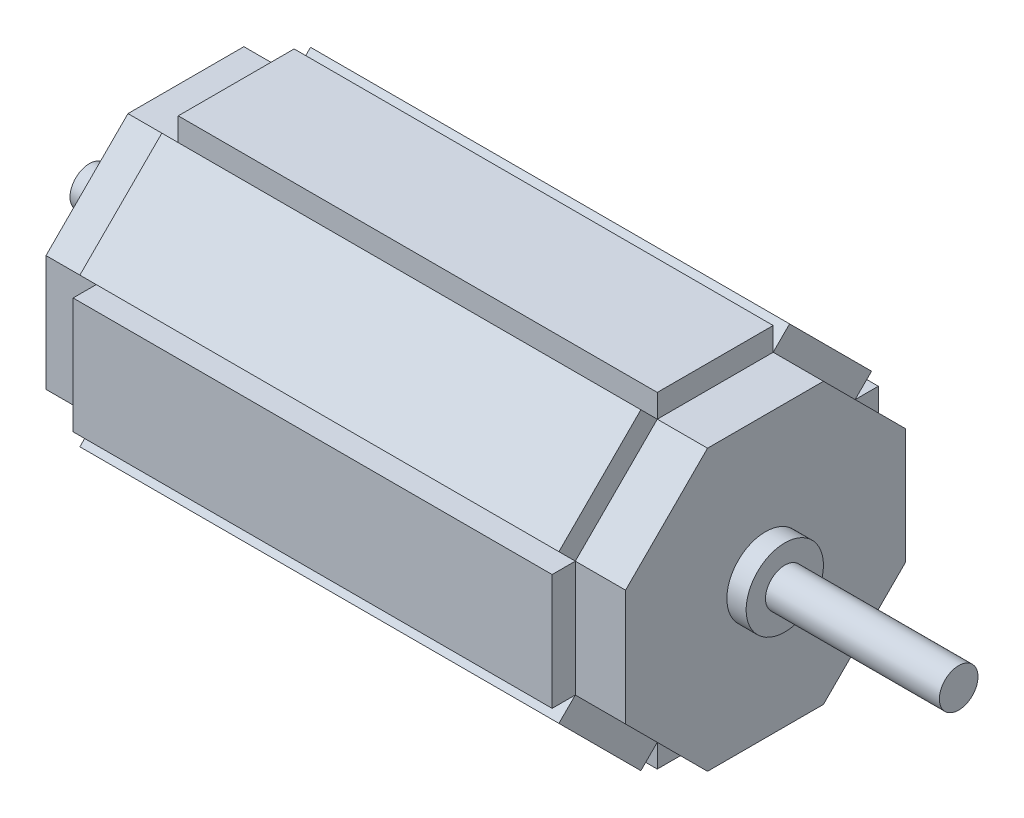
SolidWorks part; units mm, degrees
ref_plane "前视基准面" through (0, 0, 0) normal (0, 0, 1) x (1, 0, 0)
ref_plane "上视基准面" through (0, 0, 0) normal (0, 1, 0) x (1, 0, 0)
ref_plane "右视基准面" through (0, 0, 0) normal (1, 0, 0) x (0, 0, -1)
other "Configuration Table"
sketch "草图1" plane through (0, 0, 0) normal (1, 0, 0) x (0, 0, -1)
  line L1 (7.2426, -3) -> (7.2426, 3)
  line L2 (7.2426, 3) -> (3, 7.2426)
  line L3 (3, 7.2426) -> (-3, 7.2426)
  line L4 (-3, 7.2426) -> (-7.2426, 3)
  line L5 (-7.2426, 3) -> (-7.2426, -3)
  line L6 (-7.2426, -3) -> (-3, -7.2426)
  line L7 (-3, -7.2426) -> (3, -7.2426)
  line L8 (3, -7.2426) -> (7.2426, -3)
  circle A0 centre (0, 0) radius 7.2426 construction
  dimension "D1" = 6
extrude "凸台-拉伸1" add sketch "草图1" along normal blind 30
sketch "草图2" plane through (0, 7.2426, 0) normal (0, 1, 0) x (1, 0, 0)
  line L0 (9.4384, -2.3461) -> (9.352, -2.1662)
  line L1 (9.352, -2.1662) -> (9.8774, -1.7488)
  line L2 (9.8774, -1.7488) -> (9.9997, -1.8064)
  line L3 (11.1224, -1.9863) -> (11.4319, -2.0078)
  line L4 (11.4319, -2.0078) -> (11.6478, -2.0151)
  line L5 (11.6478, -2.0151) -> (11.655, -1.5833)
  line L6 (9.9134, -0.9068) -> (9.8702, -0.7341)
  line L7 (9.8702, -0.7341) -> (10.0933, -0.5901)
  line L8 (10.0933, -0.5901) -> (10.1005, -0.5829)
  line L9 (9.8126, 0.6981) -> (10.2732, 1.1299)
  line L10 (11.6406, 0.7557) -> (11.6765, 0.7629)
  line L11 (11.6765, 0.7629) -> (11.6622, 0.9284)
  line L12 (11.5902, 1.4249) -> (11.9284, 1.684)
  line L13 (11.9284, 1.684) -> (11.5686, 1.7272)
  line L14 (11.5686, 1.7272) -> (10.5467, 1.828)
  line L15 (9.6975, 1.828) -> (9.6399, 1.828)
  line L16 (9.6399, 1.828) -> (9.5247, 2.0151)
  line L17 (9.5247, 2.0151) -> (10.1365, 2.4037)
  line L18 (12.3746, 2.0367) -> (12.5186, 2.051)
  line L19 (12.5186, 2.051) -> (12.5617, 1.8711)
  line L20 (12.5617, 1.8711) -> (12.1515, 1.648)
  line L21 (12.0292, 1.1011) -> (11.9644, 0)
  line L22 (11.9788, -1.9647) -> (11.9788, -2.0294)
  line L23 (11.9788, -2.0294) -> (12.6265, -2.0294)
  line L24 (12.6265, -2.0294) -> (12.6625, -2.159)
  line L25 (12.6625, -2.159) -> (12.2451, -2.4541)
  line L26 (12.3386, -1.6264) -> (12.3962, -1.4897)
  line L27 (13.339, -1.7488) -> (13.3462, -1.3889)
  line L28 (13.3606, -0.6909) -> (12.5761, -0.5829)
  line L29 (12.5761, -0.5829) -> (12.5401, -0.4822)
  line L30 (12.5401, -0.4822) -> (12.8496, -0.2591)
  line L31 (13.2886, 0.3886) -> (13.5261, 0.6621)
  line L32 (12.792, 0.7197) -> (12.7489, 0.8564)
  line L33 (12.7489, 0.8564) -> (12.9216, 0.9715)
  line L34 (12.9216, 0.9715) -> (12.9288, 1.0579)
  line L35 (12.9288, 1.0579) -> (12.9, 1.4249)
  line L36 (12.7057, 2.0655) -> (13.0727, 2.4037)
  line L37 (13.0727, 2.4037) -> (13.1231, 2.3533)
  line L38 (13.4613, 2.1662) -> (13.6197, 2.1302)
  line L39 (14.0802, 2.0583) -> (14.4473, 2.3821)
  line L40 (14.4473, 2.3821) -> (14.548, 2.2741)
  line L41 (14.548, 2.2741) -> (14.5336, 2.2454)
  line L42 (14.3249, 0.5829) -> (14.109, 0.3742)
  line L43 (14.109, 0.3742) -> (14.0011, 0.403)
  line L44 (14.0011, 0.403) -> (14.0011, 0.5757)
  line L45 (14.0011, 0.5757) -> (13.7276, 0.6333)
  line L46 (13.7276, 0.6333) -> (13.6916, 0.5038)
  line L47 (13.6412, -1.7632) -> (13.6485, -1.8279)
  line L48 (13.6485, -1.8279) -> (14.145, -1.9215)
  line L49 (14.1306, -0.4174) -> (14.5984, -0.0648)
  line L50 (14.5984, -0.0648) -> (14.6632, -0.1799)
  line L51 (14.4473, -1.8208) -> (14.4688, -1.9791)
  line L52 (14.4688, -1.9791) -> (14.8935, -2.0223)
  line L53 (14.8935, -2.0223) -> (14.951, -2.1086)
  line L54 (14.951, -2.1086) -> (14.5336, -2.3605)
  line L55 (11.6765, -0.6837) -> (11.6765, 0.4534)
  line L56 (11.2303, 0.511) -> (10.777, 0.5613)
  line L57 (10.777, 0.5613) -> (10.3164, 0.5829)
  line L58 (11.3527, -0.6909) -> (11.6765, -0.6837)
  line L59 (8.6618, -2.4842) -> (8.6618, 2.5158) construction
  spline S0 degree 3 poles (12.2451, -2.4541) (11.9788, -2.3917) (11.4463, -2.2669) (10.5755, -2.2669) knots 0 0 0 0 1 1 1 1
  spline S1 degree 3 poles (10.5755, -2.2669) (10.3955, -2.2669) (10.0357, -2.2669) (9.4384, -2.3461) knots 1 1 1 1 2 2 2 2
  spline S2 degree 3 poles (9.9997, -1.8064) (10.0765, -1.8399) (10.23, -1.9071) (10.669, -1.9503) knots 5 5 5 5 6 6 6 6
  spline S3 degree 3 poles (10.669, -1.9503) (10.7698, -1.9599) (10.9713, -1.9791) (11.1224, -1.9863) knots 6 6 6 6 7 7 7 7
  spline S4 degree 3 poles (11.655, -1.5833) (11.6598, -1.4537) (11.6694, -1.1946) (11.6622, -1.0003) knots 10 10 10 10 11 11 11 11
  spline S5 degree 3 poles (11.6622, -1.0003) (11.4631, -0.962) (11.0648, -0.8852) (10.4315, -0.8852) knots 11 11 11 11 12 12 12 12
  spline S6 degree 3 poles (10.4315, -0.8852) (10.3452, -0.8852) (10.1725, -0.8852) (9.9134, -0.9068) knots 12 12 12 12 13 13 13 13
  spline S7 degree 3 poles (10.1005, -0.5829) (10.0981, -0.523) (10.0933, -0.403) (10.0789, -0.2123) knots 16 16 16 16 17 17 17 17
  spline S8 degree 3 poles (10.0789, -0.2123) (10.0741, -0.1487) (10.0645, -0.0216) (10.0285, 0.1295) knots 17 17 17 17 18 18 18 18
  spline S9 degree 3 poles (10.0285, 0.1295) (10.0165, 0.1967) (9.9925, 0.331) (9.9494, 0.4606) knots 18 18 18 18 19 19 19 19
  spline S10 degree 3 poles (9.9494, 0.4606) (9.9349, 0.5038) (9.9062, 0.5901) (9.8126, 0.6981) knots 19 19 19 19 20 20 20 20
  spline S11 degree 3 poles (10.2732, 1.1299) (10.3356, 1.0675) (10.4603, 0.9428) (10.7194, 0.878) knots 21 21 21 21 22 22 22 22
  spline S12 degree 3 poles (10.7194, 0.878) (10.8417, 0.8468) (11.0864, 0.7844) (11.6406, 0.7557) knots 22 22 22 22 23 23 23 23
  spline S13 degree 3 poles (11.6622, 0.9284) (11.6598, 0.9692) (11.655, 1.0507) (11.6406, 1.1839) knots 25 25 25 25 26 26 26 26
  spline S14 degree 3 poles (11.6406, 1.1839) (11.6358, 1.2283) (11.6262, 1.317) (11.5902, 1.4249) knots 26 26 26 26 27 27 27 27
  spline S15 degree 3 poles (10.5467, 1.828) (10.4747, 1.8351) (10.3308, 1.8495) (10.1221, 1.8495) knots 30 30 30 30 31 31 31 31
  spline S16 degree 3 poles (10.1221, 1.8495) (10.0477, 1.8495) (9.899, 1.8495) (9.6975, 1.828) knots 31 31 31 31 32 32 32 32
  spline S17 degree 3 poles (10.1365, 2.4037) (10.2036, 2.3365) (10.338, 2.2022) (10.6978, 2.1158) knots 35 35 35 35 36 36 36 36
  spline S18 degree 3 poles (10.6978, 2.1158) (10.7793, 2.0966) (10.9425, 2.0583) (11.2879, 2.0367) knots 36 36 36 36 37 37 37 37
  spline S19 degree 3 poles (11.2879, 2.0367) (11.3719, 2.0271) (11.5398, 2.0079) (11.8565, 2.0079) knots 37 37 37 37 38 38 38 38
  spline S20 degree 3 poles (11.8565, 2.0079) (11.9524, 2.0079) (12.1443, 2.0079) (12.3746, 2.0367) knots 38 38 38 38 39 39 39 39
  spline S21 degree 3 poles (12.1515, 1.648) (12.1179, 1.5641) (12.0508, 1.3962) (12.0292, 1.1011) knots 42 42 42 42 43 43 43 43
  spline S22 degree 3 poles (11.9644, 0) (11.962, -0.0911) (11.9572, -0.2735) (11.9572, -0.8132) knots 44 44 44 44 45 45 45 45
  spline S23 degree 3 poles (11.9572, -0.8132) (11.9572, -1.0051) (11.9572, -1.3889) (11.9788, -1.9647) knots 45 45 45 45 46 46 46 46
  spline S24 degree 3 poles (14.5336, -2.3605) (14.3705, -2.2981) (14.0442, -2.1734) (13.0511, -1.8567) knots 0 0 0 0 1 1 1 1
  spline S25 degree 3 poles (13.0511, -1.8567) (12.9719, -1.8327) (12.8136, -1.7848) (12.3386, -1.6264) knots 1 1 1 1 2 2 2 2
  spline S26 degree 3 poles (12.3962, -1.4897) (12.5665, -1.5401) (12.9072, -1.6409) (13.339, -1.7488) knots 3 3 3 3 4 4 4 4
  spline S27 degree 3 poles (13.3462, -1.3889) (13.3534, -1.257) (13.3678, -0.9931) (13.3606, -0.6909) knots 5 5 5 5 6 6 6 6
  spline S28 degree 3 poles (12.8496, -0.2591) (12.8832, -0.2927) (12.9504, -0.3598) (13.0727, -0.4066) knots 9 9 9 9 10 10 10 10
  spline S29 degree 3 poles (13.0727, -0.4066) (13.1135, -0.4222) (13.195, -0.4534) (13.3678, -0.475) knots 10 10 10 10 11 11 11 11
  spline S30 degree 3 poles (13.3678, -0.475) (13.3678, -0.3022) (13.3678, 0.0432) (13.2886, 0.3886) knots 11 11 11 11 12 12 12 12
  spline S31 degree 3 poles (13.5261, 0.6621) (13.3918, 0.6813) (13.1231, 0.7197) (12.792, 0.7197) knots 13 13 13 13 14 14 14 14
  spline S32 degree 3 poles (12.9, 1.4249) (12.8928, 1.4945) (12.8784, 1.6336) (12.8388, 1.7848) knots 18 18 18 18 19 19 19 19
  spline S33 degree 3 poles (12.8388, 1.7848) (12.8256, 1.8351) (12.7993, 1.9359) (12.7057, 2.0655) knots 19 19 19 19 20 20 20 20
  spline S34 degree 3 poles (13.1231, 2.3533) (13.1711, 2.3101) (13.267, 2.2238) (13.4613, 2.1662) knots 22 22 22 22 23 23 23 23
  spline S35 degree 3 poles (13.6197, 2.1302) (13.6916, 2.1134) (13.8355, 2.0798) (14.0802, 2.0583) knots 24 24 24 24 25 25 25 25
  spline S36 degree 3 poles (14.5336, 2.2454) (14.5049, 2.1926) (14.4473, 2.087) (14.4113, 1.9143) knots 28 28 28 28 29 29 29 29
  spline S37 degree 3 poles (14.4113, 1.9143) (14.3969, 1.8472) (14.3681, 1.7128) (14.3465, 1.4897) knots 29 29 29 29 30 30 30 30
  spline S38 degree 3 poles (14.3465, 1.4897) (14.3321, 1.3602) (14.3033, 1.1011) (14.3033, 0.9068) knots 30 30 30 30 31 31 31 31
  spline S39 degree 3 poles (14.3033, 0.9068) (14.3033, 0.854) (14.3033, 0.7484) (14.3249, 0.5829) knots 31 31 31 31 32 32 32 32
  spline S40 degree 3 poles (13.6916, 0.5038) (13.6652, 0.4126) (13.6125, 0.2303) (13.6125, -0.1727) knots 37 37 37 37 38 38 38 38
  spline S41 degree 3 poles (13.6125, -0.1727) (13.6101, -0.2207) (13.6053, -0.3167) (13.6053, -0.5973) knots 38 38 38 38 39 39 39 39
  spline S42 degree 3 poles (13.6053, -0.5973) (13.6053, -0.77) (13.6053, -1.1155) (13.6412, -1.7632) knots 39 39 39 39 40 40 40 40
  spline S43 degree 3 poles (14.145, -1.9215) (14.1546, -1.8663) (14.1738, -1.756) (14.1882, -1.4321) knots 42 42 42 42 43 43 43 43
  spline S44 degree 3 poles (14.1882, -1.4321) (14.193, -1.3458) (14.2026, -1.1731) (14.2026, -1.0507) knots 43 43 43 43 44 44 44 44
  spline S45 degree 3 poles (14.2026, -1.0507) (14.2026, -0.938) (14.2026, -0.7125) (14.1306, -0.4174) knots 44 44 44 44 45 45 45 45
  spline S46 degree 3 poles (14.6632, -0.1799) (14.6296, -0.2303) (14.5624, -0.331) (14.5192, -0.439) knots 47 47 47 47 48 48 48 48
  spline S47 degree 3 poles (14.5192, -0.439) (14.5049, -0.475) (14.4761, -0.5469) (14.4617, -0.7125) knots 48 48 48 48 49 49 49 49
  spline S48 degree 3 poles (14.4617, -0.7125) (14.4521, -0.8084) (14.4329, -1.0003) (14.4329, -1.353) knots 49 49 49 49 50 50 50 50
  spline S49 degree 3 poles (14.4329, -1.353) (14.4329, -1.4561) (14.4329, -1.6624) (14.4473, -1.8208) knots 50 50 50 50 51 51 51 51
  spline S50 degree 3 poles (14.0227, 0.8132) (14.0467, 1.0051) (14.0946, 1.3889) (14.0874, 1.8136) knots 4 4 4 4 5 5 5 5
  spline S51 degree 3 poles (13.2382, 0.9715) (13.3414, 0.9404) (13.5477, 0.878) (14.0227, 0.8132) knots 3 3 3 3 4 4 4 4
  spline S52 degree 3 poles (13.1591, 1.9503) (13.1663, 1.7608) (13.1807, 1.3818) (13.2382, 0.9715) knots 2 2 2 2 3 3 3 3
  spline S53 degree 3 poles (13.6448, 1.8999) (13.5141, 1.9191) (13.2526, 1.9575) (13.1591, 1.9503) knots 1 1 1 1 2 2 2 2
  spline S54 degree 3 poles (14.0874, 1.8136) (14.0706, 1.8231) (14.0371, 1.8424) (13.6448, 1.8999) knots 0 0 0 0 1 1 1 1
  spline S55 degree 3 poles (11.6765, 0.4534) (11.6286, 0.463) (11.5326, 0.4822) (11.2303, 0.511) knots 1 1 1 1 2 2 2 2
  spline S56 degree 3 poles (10.3164, 0.5829) (10.3164, 0.355) (10.3164, -0.1007) (10.4171, -0.5326) knots 4 4 4 4 5 5 5 5
  spline S57 degree 3 poles (10.4171, -0.5326) (10.4555, -0.5494) (10.5323, -0.5829) (10.669, -0.6189) knots 5 5 5 5 6 6 6 6
  spline S58 degree 3 poles (10.669, -0.6189) (10.7194, -0.6309) (10.8201, -0.6549) (11.0001, -0.6693) knots 6 6 6 6 7 7 7 7
  spline S59 degree 3 poles (11.0001, -0.6693) (11.06, -0.6741) (11.18, -0.6837) (11.3527, -0.6909) knots 7 7 7 7 8 8 8 8
  dimension "D1" = 5
sketch "草图3" plane through (0, 7.2426, 0) normal (0, 1, 0) x (1, 0, 0)
  line L0 (16.0742, -2.3589) -> (15.9878, -2.179)
  line L1 (15.9878, -2.179) -> (16.5131, -1.7616)
  line L2 (16.5131, -1.7616) -> (16.6355, -1.8191)
  line L3 (17.7582, -1.999) -> (18.0677, -2.0206)
  line L4 (18.0677, -2.0206) -> (18.2836, -2.0278)
  line L5 (18.2836, -2.0278) -> (18.2908, -1.596)
  line L6 (16.5492, -0.9195) -> (16.506, -0.7468)
  line L7 (16.506, -0.7468) -> (16.7291, -0.6029)
  line L8 (16.7291, -0.6029) -> (16.7363, -0.5957)
  line L9 (16.4484, 0.6853) -> (16.909, 1.1171)
  line L10 (18.2763, 0.7429) -> (18.3123, 0.7501)
  line L11 (18.3123, 0.7501) -> (18.2979, 0.9156)
  line L12 (18.226, 1.4122) -> (18.5642, 1.6713)
  line L13 (18.5642, 1.6713) -> (18.2044, 1.7144)
  line L14 (18.2044, 1.7144) -> (17.1825, 1.8152)
  line L15 (16.3332, 1.8152) -> (16.2757, 1.8152)
  line L16 (16.2757, 1.8152) -> (16.1605, 2.0023)
  line L17 (16.1605, 2.0023) -> (16.7723, 2.3909)
  line L18 (19.0104, 2.0239) -> (19.1544, 2.0383)
  line L19 (19.1544, 2.0383) -> (19.1975, 1.8584)
  line L20 (19.1975, 1.8584) -> (18.7873, 1.6353)
  line L21 (18.665, 1.0883) -> (18.6002, -0.0128)
  line L22 (18.6146, -1.9774) -> (18.6146, -2.0422)
  line L23 (18.6146, -2.0422) -> (19.2623, -2.0422)
  line L24 (19.2623, -2.0422) -> (19.2983, -2.1717)
  line L25 (19.2983, -2.1717) -> (18.8809, -2.4668)
  line L26 (18.9744, -1.6392) -> (19.032, -1.5025)
  line L27 (19.9748, -1.7616) -> (19.9819, -1.4017)
  line L28 (19.9964, -0.7036) -> (19.2119, -0.5957)
  line L29 (19.2119, -0.5957) -> (19.1759, -0.4949)
  line L30 (19.1759, -0.4949) -> (19.4854, -0.2718)
  line L31 (19.9244, 0.3759) -> (20.1619, 0.6493)
  line L32 (19.4278, 0.7069) -> (19.3847, 0.8436)
  line L33 (19.3847, 0.8436) -> (19.5574, 0.9588)
  line L34 (19.5574, 0.9588) -> (19.5646, 1.0451)
  line L35 (19.5646, 1.0451) -> (19.5358, 1.4122)
  line L36 (19.3415, 2.0527) -> (19.7085, 2.3909)
  line L37 (19.7085, 2.3909) -> (19.7589, 2.3406)
  line L38 (20.0971, 2.1534) -> (20.2554, 2.1175)
  line L39 (20.716, 2.0455) -> (21.0831, 2.3693)
  line L40 (21.0831, 2.3693) -> (21.1838, 2.2614)
  line L41 (21.1838, 2.2614) -> (21.1694, 2.2326)
  line L42 (20.9607, 0.5702) -> (20.7448, 0.3615)
  line L43 (20.7448, 0.3615) -> (20.6369, 0.3903)
  line L44 (20.6369, 0.3903) -> (20.6369, 0.563)
  line L45 (20.6369, 0.563) -> (20.3634, 0.6206)
  line L46 (20.3634, 0.6206) -> (20.3274, 0.491)
  line L47 (20.277, -1.7759) -> (20.2842, -1.8407)
  line L48 (20.2842, -1.8407) -> (20.7808, -1.9343)
  line L49 (20.7664, -0.4302) -> (21.2342, -0.0775)
  line L50 (21.2342, -0.0775) -> (21.299, -0.1927)
  line L51 (21.0831, -1.8335) -> (21.1046, -1.9918)
  line L52 (21.1046, -1.9918) -> (21.5292, -2.035)
  line L53 (21.5292, -2.035) -> (21.5868, -2.1214)
  line L54 (21.5868, -2.1214) -> (21.1694, -2.3732)
  line L55 (18.3123, -0.6964) -> (18.3123, 0.4406)
  line L56 (17.8661, 0.4982) -> (17.4127, 0.5486)
  line L57 (17.4127, 0.5486) -> (16.9522, 0.5702)
  line L58 (17.9885, -0.7036) -> (18.3123, -0.6964)
  spline S0 degree 3 poles (18.8809, -2.4668) (18.6146, -2.4044) (18.082, -2.2797) (17.2112, -2.2797) knots 0 0 0 0 1 1 1 1
  spline S1 degree 3 poles (17.2112, -2.2797) (17.0313, -2.2797) (16.6715, -2.2797) (16.0742, -2.3589) knots 1 1 1 1 2 2 2 2
  spline S2 degree 3 poles (16.6355, -1.8191) (16.7123, -1.8527) (16.8658, -1.9199) (17.3048, -1.9631) knots 5 5 5 5 6 6 6 6
  spline S3 degree 3 poles (17.3048, -1.9631) (17.4056, -1.9726) (17.6071, -1.9918) (17.7582, -1.999) knots 6 6 6 6 7 7 7 7
  spline S4 degree 3 poles (18.2908, -1.596) (18.2955, -1.4665) (18.3051, -1.2074) (18.2979, -1.0131) knots 10 10 10 10 11 11 11 11
  spline S5 degree 3 poles (18.2979, -1.0131) (18.0988, -0.9747) (17.7006, -0.898) (17.0673, -0.898) knots 11 11 11 11 12 12 12 12
  spline S6 degree 3 poles (17.0673, -0.898) (16.9809, -0.898) (16.8082, -0.898) (16.5492, -0.9195) knots 12 12 12 12 13 13 13 13
  spline S7 degree 3 poles (16.7363, -0.5957) (16.7339, -0.5357) (16.7291, -0.4158) (16.7147, -0.2251) knots 16 16 16 16 17 17 17 17
  spline S8 degree 3 poles (16.7147, -0.2251) (16.7099, -0.1615) (16.7003, -0.0344) (16.6643, 0.1168) knots 17 17 17 17 18 18 18 18
  spline S9 degree 3 poles (16.6643, 0.1168) (16.6523, 0.184) (16.6283, 0.3183) (16.5851, 0.4478) knots 18 18 18 18 19 19 19 19
  spline S10 degree 3 poles (16.5851, 0.4478) (16.5707, 0.491) (16.542, 0.5774) (16.4484, 0.6853) knots 19 19 19 19 20 20 20 20
  spline S11 degree 3 poles (16.909, 1.1171) (16.9713, 1.0548) (17.0961, 0.93) (17.3552, 0.8652) knots 21 21 21 21 22 22 22 22
  spline S12 degree 3 poles (17.3552, 0.8652) (17.4775, 0.834) (17.7222, 0.7717) (18.2763, 0.7429) knots 22 22 22 22 23 23 23 23
  spline S13 degree 3 poles (18.2979, 0.9156) (18.2955, 0.9564) (18.2908, 1.038) (18.2763, 1.1711) knots 25 25 25 25 26 26 26 26
  spline S14 degree 3 poles (18.2763, 1.1711) (18.2716, 1.2155) (18.2619, 1.3042) (18.226, 1.4122) knots 26 26 26 26 27 27 27 27
  spline S15 degree 3 poles (17.1825, 1.8152) (17.1105, 1.8224) (16.9665, 1.8368) (16.7578, 1.8368) knots 30 30 30 30 31 31 31 31
  spline S16 degree 3 poles (16.7578, 1.8368) (16.6835, 1.8368) (16.5348, 1.8368) (16.3332, 1.8152) knots 31 31 31 31 32 32 32 32
  spline S17 degree 3 poles (16.7723, 2.3909) (16.8394, 2.3238) (16.9737, 2.1894) (17.3336, 2.1031) knots 35 35 35 35 36 36 36 36
  spline S18 degree 3 poles (17.3336, 2.1031) (17.4151, 2.0839) (17.5783, 2.0455) (17.9237, 2.0239) knots 36 36 36 36 37 37 37 37
  spline S19 degree 3 poles (17.9237, 2.0239) (18.0077, 2.0143) (18.1756, 1.9951) (18.4923, 1.9951) knots 37 37 37 37 38 38 38 38
  spline S20 degree 3 poles (18.4923, 1.9951) (18.5882, 1.9951) (18.7801, 1.9951) (19.0104, 2.0239) knots 38 38 38 38 39 39 39 39
  spline S21 degree 3 poles (18.7873, 1.6353) (18.7537, 1.5513) (18.6866, 1.3834) (18.665, 1.0883) knots 42 42 42 42 43 43 43 43
  spline S22 degree 3 poles (18.6002, -0.0128) (18.5978, -0.1039) (18.593, -0.2862) (18.593, -0.826) knots 44 44 44 44 45 45 45 45
  spline S23 degree 3 poles (18.593, -0.826) (18.593, -1.0179) (18.593, -1.4017) (18.6146, -1.9774) knots 45 45 45 45 46 46 46 46
  spline S24 degree 3 poles (21.1694, -2.3732) (21.0063, -2.3109) (20.68, -2.1862) (19.6869, -1.8695) knots 0 0 0 0 1 1 1 1
  spline S25 degree 3 poles (19.6869, -1.8695) (19.6077, -1.8455) (19.4494, -1.7975) (18.9744, -1.6392) knots 1 1 1 1 2 2 2 2
  spline S26 degree 3 poles (19.032, -1.5025) (19.2023, -1.5528) (19.543, -1.6536) (19.9748, -1.7616) knots 3 3 3 3 4 4 4 4
  spline S27 degree 3 poles (19.9819, -1.4017) (19.9892, -1.2698) (20.0036, -1.0059) (19.9964, -0.7036) knots 5 5 5 5 6 6 6 6
  spline S28 degree 3 poles (19.4854, -0.2718) (19.519, -0.3054) (19.5861, -0.3726) (19.7085, -0.4194) knots 9 9 9 9 10 10 10 10
  spline S29 degree 3 poles (19.7085, -0.4194) (19.7492, -0.4349) (19.8308, -0.4661) (20.0036, -0.4877) knots 10 10 10 10 11 11 11 11
  spline S30 degree 3 poles (20.0036, -0.4877) (20.0036, -0.315) (20.0036, 0.0304) (19.9244, 0.3759) knots 11 11 11 11 12 12 12 12
  spline S31 degree 3 poles (20.1619, 0.6493) (20.0275, 0.6685) (19.7589, 0.7069) (19.4278, 0.7069) knots 13 13 13 13 14 14 14 14
  spline S32 degree 3 poles (19.5358, 1.4122) (19.5286, 1.4818) (19.5142, 1.6209) (19.4746, 1.772) knots 18 18 18 18 19 19 19 19
  spline S33 degree 3 poles (19.4746, 1.772) (19.4614, 1.8224) (19.435, 1.9232) (19.3415, 2.0527) knots 19 19 19 19 20 20 20 20
  spline S34 degree 3 poles (19.7589, 2.3406) (19.8068, 2.2974) (19.9028, 2.211) (20.0971, 2.1534) knots 22 22 22 22 23 23 23 23
  spline S35 degree 3 poles (20.2554, 2.1175) (20.3274, 2.1007) (20.4713, 2.0671) (20.716, 2.0455) knots 24 24 24 24 25 25 25 25
  spline S36 degree 3 poles (21.1694, 2.2326) (21.1406, 2.1798) (21.0831, 2.0743) (21.0471, 1.9016) knots 28 28 28 28 29 29 29 29
  spline S37 degree 3 poles (21.0471, 1.9016) (21.0327, 1.8344) (21.0039, 1.7001) (20.9823, 1.477) knots 29 29 29 29 30 30 30 30
  spline S38 degree 3 poles (20.9823, 1.477) (20.9679, 1.3474) (20.9391, 1.0883) (20.9391, 0.894) knots 30 30 30 30 31 31 31 31
  spline S39 degree 3 poles (20.9391, 0.894) (20.9391, 0.8413) (20.9391, 0.7357) (20.9607, 0.5702) knots 31 31 31 31 32 32 32 32
  spline S40 degree 3 poles (20.3274, 0.491) (20.301, 0.3998) (20.2482, 0.2176) (20.2482, -0.1855) knots 37 37 37 37 38 38 38 38
  spline S41 degree 3 poles (20.2482, -0.1855) (20.2458, -0.2334) (20.2411, -0.3294) (20.2411, -0.6101) knots 38 38 38 38 39 39 39 39
  spline S42 degree 3 poles (20.2411, -0.6101) (20.2411, -0.7828) (20.2411, -1.1282) (20.277, -1.7759) knots 39 39 39 39 40 40 40 40
  spline S43 degree 3 poles (20.7808, -1.9343) (20.7904, -1.8791) (20.8096, -1.7687) (20.8239, -1.4449) knots 42 42 42 42 43 43 43 43
  spline S44 degree 3 poles (20.8239, -1.4449) (20.8288, -1.3585) (20.8384, -1.1858) (20.8384, -1.0635) knots 43 43 43 43 44 44 44 44
  spline S45 degree 3 poles (20.8384, -1.0635) (20.8384, -0.9507) (20.8384, -0.7252) (20.7664, -0.4302) knots 44 44 44 44 45 45 45 45
  spline S46 degree 3 poles (21.299, -0.1927) (21.2654, -0.243) (21.1982, -0.3438) (21.155, -0.4517) knots 47 47 47 47 48 48 48 48
  spline S47 degree 3 poles (21.155, -0.4517) (21.1406, -0.4877) (21.1118, -0.5597) (21.0975, -0.7252) knots 48 48 48 48 49 49 49 49
  spline S48 degree 3 poles (21.0975, -0.7252) (21.0878, -0.8212) (21.0686, -1.0131) (21.0686, -1.3657) knots 49 49 49 49 50 50 50 50
  spline S49 degree 3 poles (21.0686, -1.3657) (21.0686, -1.4689) (21.0686, -1.6752) (21.0831, -1.8335) knots 50 50 50 50 51 51 51 51
  spline S50 degree 3 poles (20.6584, 0.8005) (20.6825, 0.9924) (20.7304, 1.3762) (20.7232, 1.8008) knots 4 4 4 4 5 5 5 5
  spline S51 degree 3 poles (19.874, 0.9588) (19.9772, 0.9276) (20.1835, 0.8652) (20.6584, 0.8005) knots 3 3 3 3 4 4 4 4
  spline S52 degree 3 poles (19.7948, 1.9376) (19.802, 1.748) (19.8164, 1.369) (19.874, 0.9588) knots 2 2 2 2 3 3 3 3
  spline S53 degree 3 poles (20.2806, 1.8872) (20.1499, 1.9064) (19.8884, 1.9447) (19.7948, 1.9376) knots 1 1 1 1 2 2 2 2
  spline S54 degree 3 poles (20.7232, 1.8008) (20.7064, 1.8104) (20.6728, 1.8296) (20.2806, 1.8872) knots 0 0 0 0 1 1 1 1
  spline S55 degree 3 poles (18.3123, 0.4406) (18.2643, 0.4503) (18.1684, 0.4694) (17.8661, 0.4982) knots 1 1 1 1 2 2 2 2
  spline S56 degree 3 poles (16.9522, 0.5702) (16.9522, 0.3423) (16.9522, -0.1135) (17.0529, -0.5453) knots 4 4 4 4 5 5 5 5
  spline S57 degree 3 poles (17.0529, -0.5453) (17.0913, -0.5621) (17.1681, -0.5957) (17.3048, -0.6317) knots 5 5 5 5 6 6 6 6
  spline S58 degree 3 poles (17.3048, -0.6317) (17.3552, -0.6437) (17.4559, -0.6676) (17.6359, -0.682) knots 6 6 6 6 7 7 7 7
  spline S59 degree 3 poles (17.6359, -0.682) (17.6958, -0.6868) (17.8158, -0.6964) (17.9885, -0.7036) knots 7 7 7 7 8 8 8 8
sketch "草图4" plane through (30, 0, 0) normal (1, 0, 0) x (0, 0, -1)
  circle A0 centre (0, 0) radius 1
  dimension "D1" = 2
extrude "凸台-拉伸2" add sketch "草图4" along normal blind 10
sketch "草图5" plane through (30, 0, 0) normal (1, 0, 0) x (0, 0, -1)
  circle A0 centre (0, 0) radius 2
  dimension "D1" = 4
extrude "凸台-拉伸3" add sketch "草图5" along normal blind 1 contours A0
sketch "草图6" plane through (0, 0, 0) normal (-1, 0, 0) x (0, 0, 1)
  circle A0 centre (0, 0) radius 1 construction
  circle A1 centre (0, 0) radius 1
extrude "凸台-拉伸4" add sketch "草图6" along normal blind 5
sketch "草图7" plane through (0, 0, 0) normal (-1, 0, 0) x (0, 0, 1)
  circle A0 centre (0, 0) radius 2 construction
  circle A1 centre (0, 0) radius 2
extrude "凸台-拉伸5" add sketch "草图7" along normal blind 1
sketch "草图8" plane through (0, 7.2426, 0) normal (0, 1, 0) x (1, 0, 0)
  line L0 (2.6018, 0) -> (27.3982, 0) construction
  line L1 (2.6018, 3) -> (27.3982, 3)
  line L2 (2.6018, 3) -> (2.6018, -3)
  line L3 (2.6018, -3) -> (27.3982, -3)
  line L4 (27.3982, 3) -> (27.3982, -3)
  line L5 (2.6018, 3) -> (27.3982, -3) construction
  line L6 (2.6018, -3) -> (27.3982, 3) construction
  line L7 (15, 0) -> (15, -3) construction
  line L9 (30, 3) -> (0, 3) construction
  point P0 (15, 0)
  point P9 (15, 3)
  dimension "D1" = 6
extrude "凸台-拉伸6" add sketch "草图8" along normal blind 1.2
pattern_circular "阵列(圆周)1" count 8 over 360 about axis through (0, 0, 0) along (1, 0, 0) of "凸台-拉伸6"
sketch "草图9" plane through (0, 0, 0) normal (1, 0, 0) x (0, 0, -1)
  line L0 (0, 0) -> (0, 9.8226) construction
